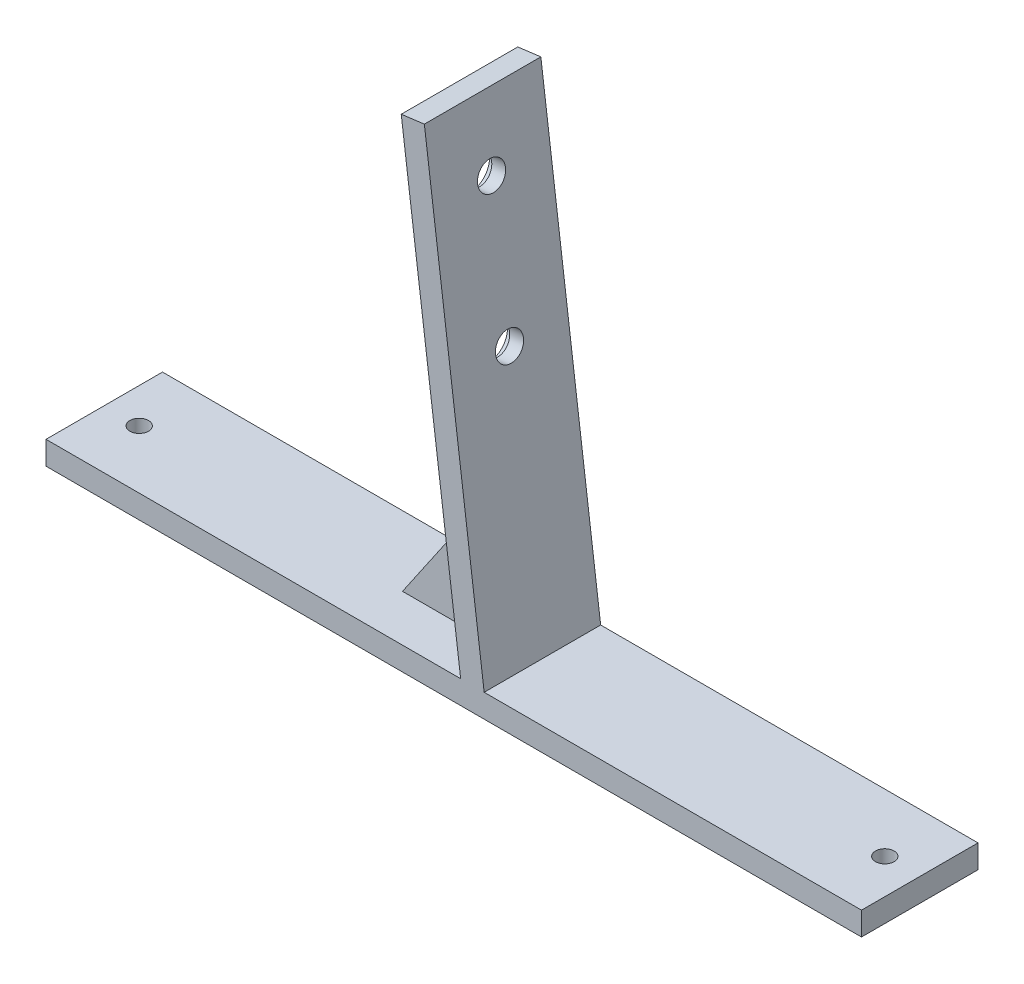
SolidWorks part; units mm, degrees
ref_plane "前视基准面" through (0, 0, 0) normal (0, 0, 1) x (1, 0, 0)
ref_plane "上视基准面" through (0, 0, 0) normal (0, 1, 0) x (1, 0, 0)
ref_plane "右视基准面" through (0, 0, 0) normal (1, 0, 0) x (0, 0, -1)
other "Configuration Table"
sketch "草图1" plane through (0, 0, 0) normal (0, 1, 0) x (1, 0, 0)
  line L1 (0, 0) -> (350, 0)
  line L2 (0, 0) -> (0, 50)
  line L3 (0, 50) -> (350, 50)
  line L4 (350, 0) -> (350, 50)
  circle A1 centre (15, 25) radius 4
  circle A2 centre (335, 25) radius 4
extrude "凸台-拉伸1" add sketch "草图1" along normal blind 10
cosmetic thread "装饰螺纹线1" parameters "D2"=10
cosmetic thread "装饰螺纹线2" parameters "D2"=10
sketch "草图2" plane through (0, 0, 0) normal (0, 0, 1) x (1, 0, 0)
  line L2 (0, 10) -> (350, 10) construction
  line L3 (170.8179, 65.2317) -> (152.4639, 207.0627)
  line L4 (133, 10) -> (170.8179, 65.2317)
  line L5 (152.4639, 207.0627) -> (162.3812, 208.3461)
  line L6 (162.3812, 208.3461) -> (188.0486, 10)
  line L7 (188.0486, 10) -> (175, 10)
  line L8 (133, 10) -> (175, 10)
  line L9 (133, 10) -> (175, 10)
  line M4 (350, 10) -> (0, 10)
extrude "凸台-拉伸2" add sketch "草图2" against normal blind 50 contours L6 L5 L3 M4
sketch "草图3" plane through (0, 0, 0) normal (0, 0, 1) x (1, 0, 0)
  line L0 (170.8179, 65.2317) -> (177.9653, 10)
  line L1 (177.9653, 10) -> (133, 10)
  line L2 (170.8179, 65.2317) -> (152.4639, 207.0627) construction
  line L3 (0, 10) -> (133, 10) construction
  line L4 (170.8179, 65.2317) -> (133, 10)
  line M10 (170.8179, 65.2317) -> (133, 10)
extrude "切除-拉伸1" cut sketch "草图3" against normal blind 20 contours L1 L0 M10
sketch "草图4" plane through (0, 0, -50) normal (0, 0, -1) x (-1, 0, 0)
  line L0 (-170.8179, 65.2317) -> (-177.9653, 10)
  line L1 (-177.9653, 10) -> (-133, 10)
  line L2 (-170.8179, 65.2317) -> (-152.4639, 207.0627) construction
  line L3 (-133, 10) -> (0, 10) construction
  line L4 (-170.8179, 65.2317) -> (-133, 10)
extrude "切除-拉伸2" cut sketch "草图4" against normal blind 20
sketch "草图5" plane through (186.2242, 24.0988, 0) normal (0.9917, 0.1283, 0) x (0, 0, -1)
  circle A0 centre (25, 95.7837) radius 6
  circle A1 centre (25, 155.7837) radius 6
extrude "切除-拉伸3" cut sketch "草图5" against normal blind 20
sketch "草图6" plane through (176.3069, 22.8154, 0) normal (-0.9917, -0.1283, 0) x (0, 0, 1)
  circle A0 centre (-25, 155.7837) radius 9
  circle A1 centre (-25, 95.7837) radius 9
extrude "切除-拉伸4" cut sketch "草图6" against normal blind 4
